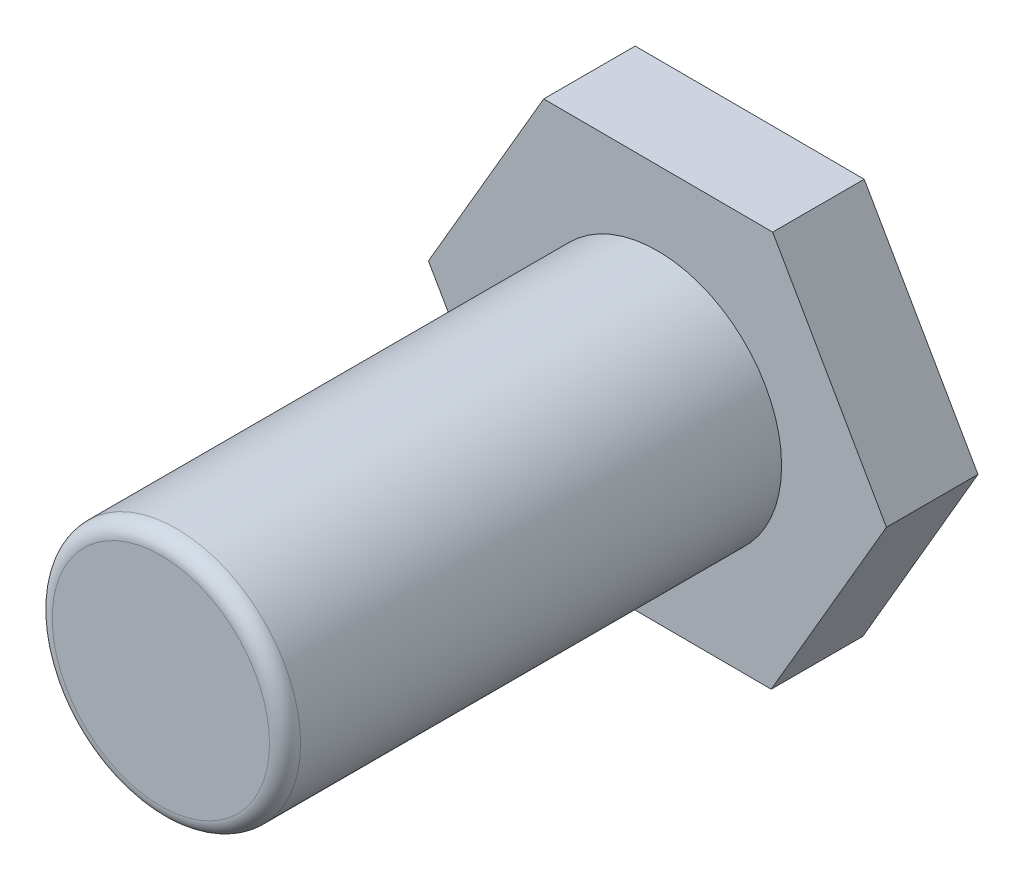
SolidWorks part; units mm, degrees
material "1.4021 (X20Cr13)"
ref_plane "Ön Düzlem" through (0, 0, 0) normal (0, 0, 1) x (1, 0, 0)
ref_plane "Üst Düzlem" through (0, 0, 0) normal (0, 1, 0) x (1, 0, 0)
ref_plane "Sağ Düzlem" through (0, 0, 0) normal (1, 0, 0) x (0, 0, -1)
sketch "Çizim2" plane through (0, 0, 0) normal (0, 0, 1) x (1, 0, 0)
  line L1 (3.7128, 6.3763) -> (-3.6656, 6.4036)
  line L2 (-3.6656, 6.4036) -> (-7.3785, 0.0273)
  line L3 (-7.3785, 0.0273) -> (-3.7128, -6.3763)
  line L4 (-3.7128, -6.3763) -> (3.6656, -6.4036)
  line L5 (3.6656, -6.4036) -> (7.3785, -0.0273)
  line L6 (7.3785, -0.0273) -> (3.7128, 6.3763)
  circle A0 centre (0, 0) radius 6.39 construction
  dimension "D1" = 12.78
extrude "Yükseklik-Ekstrüzyon1" add sketch "Çizim2" along normal blind 2.95
sketch "Çizim3" plane through (0, 0, 2.95) normal (0, 0, 1) x (1, 0, 0)
  circle A0 centre (0, 0) radius 4
  dimension "D1" = 8
extrude "Yükseklik-Ekstrüzyon2" add sketch "Çizim3" along normal blind 16
cosmetic thread "Kozmetik Diş Açma1" parameters "D2"=6.619
fillet "Radyus3" radius 0.5 1 edges at (4, 0, 18.95)
